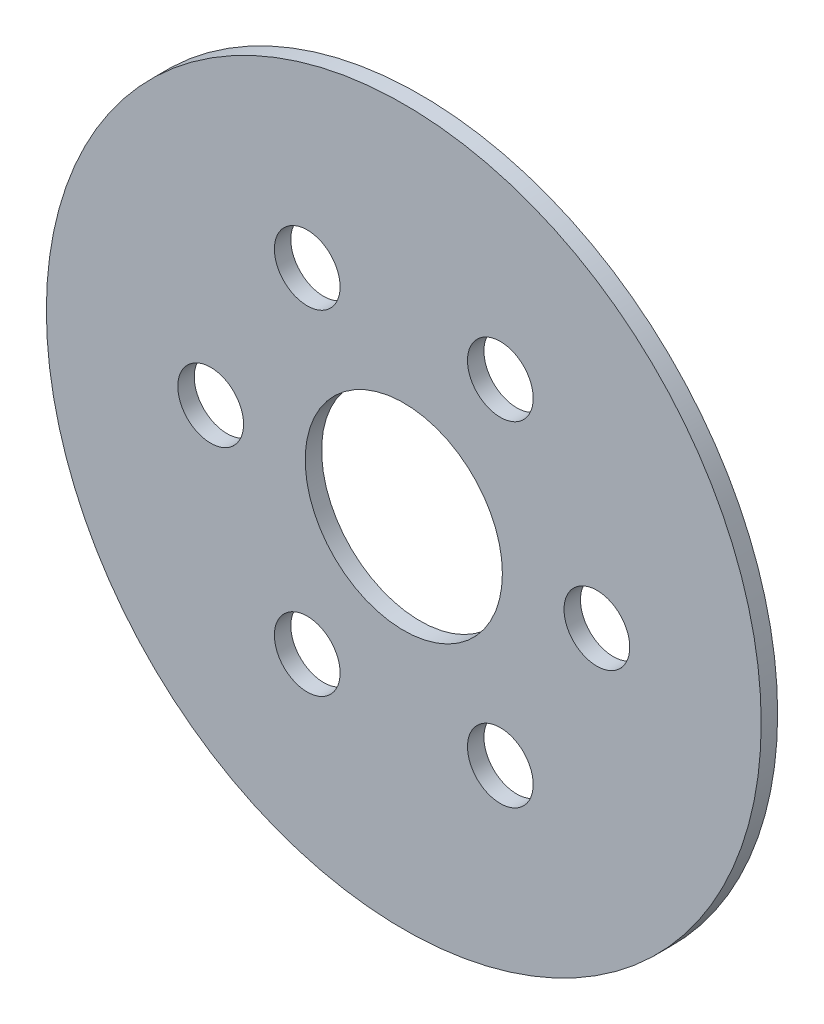
SolidWorks part; units mm, degrees
ref_plane "Ebene vorne" through (0, 0, 0) normal (0, 0, 1) x (1, 0, 0)
ref_plane "Ebene oben" through (0, 0, 0) normal (0, 1, 0) x (1, 0, 0)
ref_plane "Ebene rechts" through (0, 0, 0) normal (1, 0, 0) x (0, 0, -1)
sketch "Skizze1" plane through (0, 0, 0) normal (0, 0, 1) x (1, 0, 0)
  line L0 (0, 0) -> (11.75, 0) construction
  circle A0 centre (0, 0) radius 21.75
  circle A2 centre (11.75, 0) radius 2
  circle A3 centre (5.875, -10.1758) radius 2
  circle A4 centre (-5.875, -10.1758) radius 2
  circle A5 centre (-11.75, 0) radius 2
  circle A6 centre (-5.875, 10.1758) radius 2
  circle A7 centre (5.875, 10.1758) radius 2
  circle A8 centre (0, 0) radius 6
  point P18 (0, 0)
  dimension "D1" = 43.5
  dimension "D3" = 6
  dimension "D4" = 12
  dimension "D2" = 11.75
extrude "Aufsatz-Linear austragen1" add sketch "Skizze1" along normal blind 1
